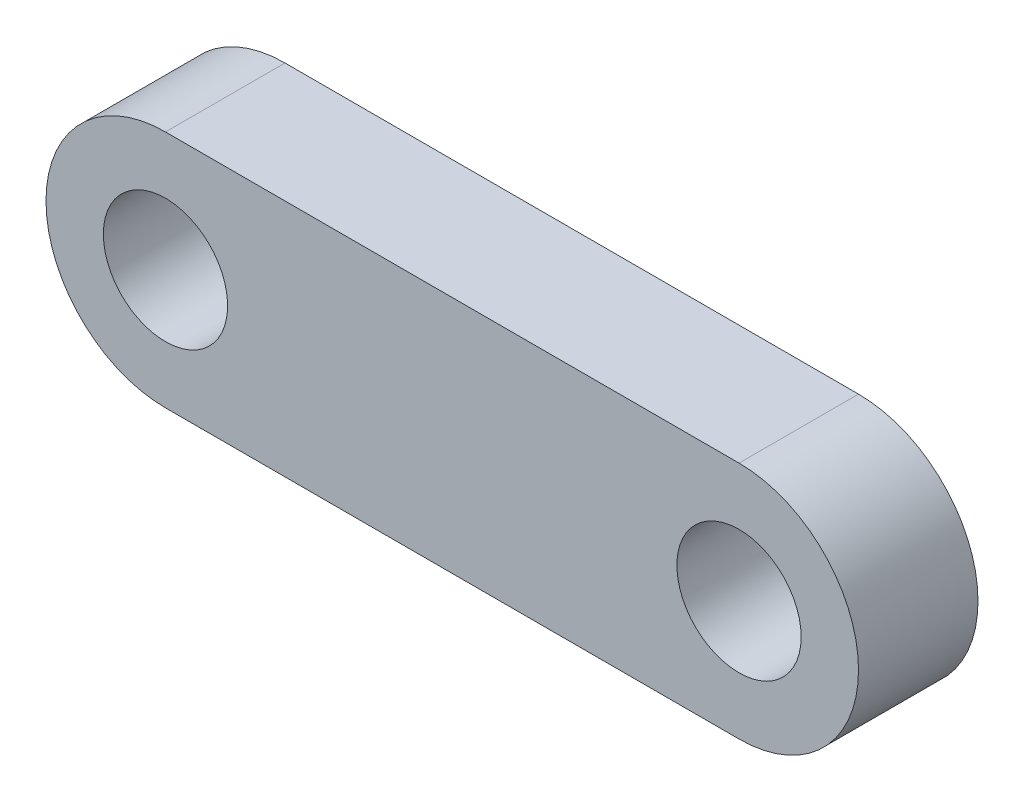
SolidWorks part; units mm, degrees
ref_plane "Front Plane" through (0, 0, 0) normal (0, 0, 1) x (1, 0, 0)
ref_plane "Top Plane" through (0, 0, 0) normal (0, 1, 0) x (1, 0, 0)
ref_plane "Right Plane" through (0, 0, 0) normal (1, 0, 0) x (0, 0, -1)
sketch "Sketch1" plane through (0, 0, 0) normal (0, 0, 1) x (1, 0, 0)
  line L1 (-71.1789, 3.175) -> (-55.9389, 3.175)
  line L2 (-63.5589, 3.175) -> (-63.5589, -2.7618) construction
  line L3 (-71.1789, -3.175) -> (-55.9389, -3.175)
  arc A0 (-55.9389, 3.175) -> (-55.9389, -3.175) centre (-55.9389, 0) cw
  arc A1 (-71.1789, 3.175) -> (-71.1789, -3.175) centre (-71.1789, 0) ccw
  circle A2 centre (-55.9389, 0) radius 1.651
  circle A3 centre (-71.1789, 0) radius 1.651
  dimension "D3" = 3.302
  dimension "D2" = 15.24
extrude "Boss-Extrude1" add sketch "Sketch1" along normal blind 3.175
